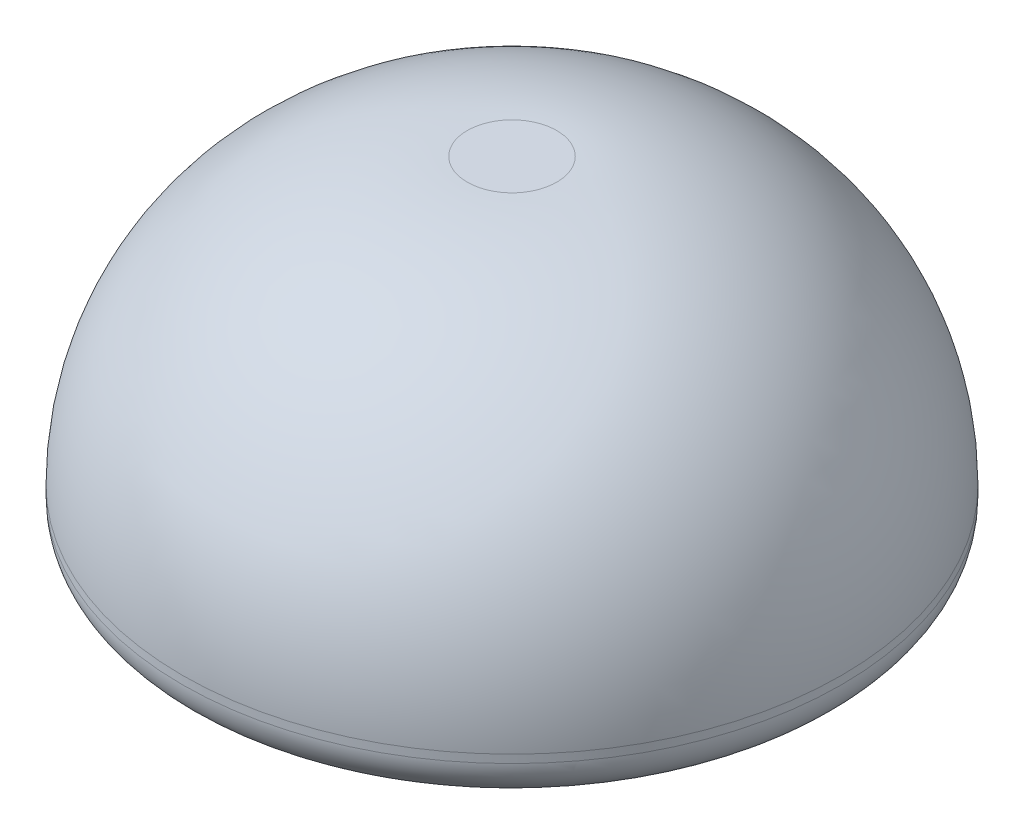
SolidWorks part; units mm, degrees
material "Glass"
ref_plane "Front Plane" through (0, 0, 0) normal (0, 0, 1) x (1, 0, 0)
ref_plane "Top Plane" through (0, 0, 0) normal (0, 1, 0) x (1, 0, 0)
ref_plane "Right Plane" through (0, 0, 0) normal (1, 0, 0) x (0, 0, -1)
sketch "Sketch1" plane through (0, 0, 0) normal (0, 1, 0) x (1, 0, 0)
  circle A0 centre (0, 0) radius 8.1
  dimension "D1" = 16.2
extrude "Boss-Extrude1" add sketch "Sketch1" along normal blind 8.2
fillet "Fillet2" radius 7 1 edges at (0, 8.2, 8.1)
fillet "Fillet3" radius 1 1 edges at (0, 0, 8.1)
equation "\"diameter\"= 14.1"
